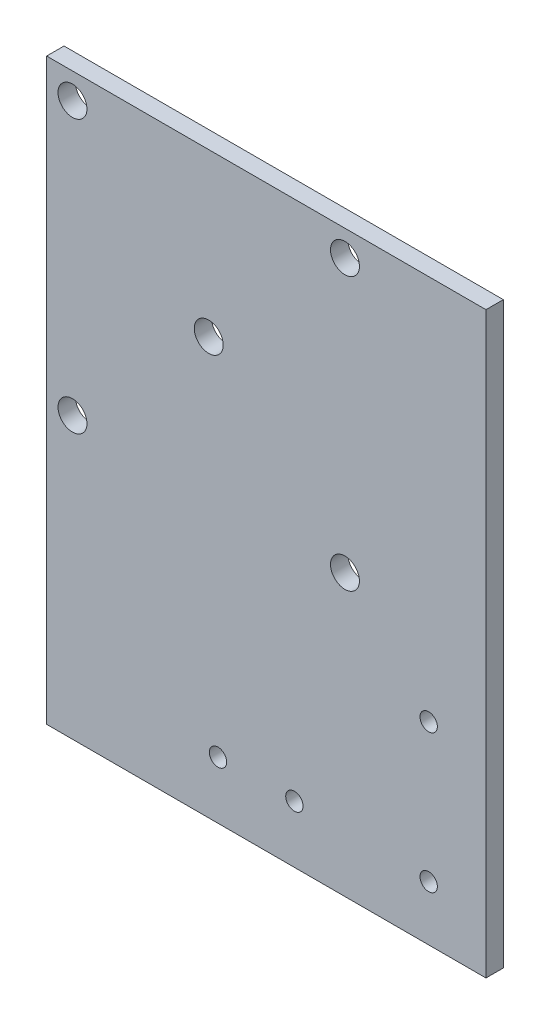
SolidWorks part; units mm, degrees
ref_plane "Front Plane" through (0, 0, 0) normal (0, 0, 1) x (1, 0, 0)
ref_plane "Top Plane" through (0, 0, 0) normal (0, 1, 0) x (1, 0, 0)
ref_plane "Right Plane" through (0, 0, 0) normal (1, 0, 0) x (0, 0, -1)
sketch "Sketch1" plane through (0, 0, 0) normal (0, 0, 1) x (1, 0, 0)
  line L1 (0, 0) -> (75.9, 0)
  line L2 (0, 0) -> (0, 100)
  line L3 (0, 100) -> (75.9, 100)
  line L4 (75.9, 0) -> (75.9, 100)
  dimension "D1" = 75.9
  dimension "D2" = 100
extrude "Boss-Extrude1" add sketch "Sketch1" along normal blind 3
sketch "Sketch2" plane through (0, 0, 0) normal (0, 0, -1) x (-1, 0, 0)
  circle A0 centre (-51.5386, 95.5386) radius 2.5
  circle A1 centre (-4.4614, 95.5386) radius 2.5
  circle A2 centre (-4.4614, 48.4614) radius 2.5
  circle A3 centre (-51.5386, 48.4614) radius 2.5
  dimension "D1" = 5
extrude "Cut-Extrude1" cut sketch "Sketch2" against normal blind 10
sketch "Sketch5" plane through (0, 0, 3) normal (0, 0, 1) x (1, 0, 0)
  line L0 (66, 0) -> (66, 100) construction
  line L1 (0, 0) -> (75.9, 0) construction
  line L2 (75.9, 100) -> (0, 100) construction
  line L3 (64.0784, 0) -> (67.9216, 0) construction
  line L4 (67.9216, 55.9706) -> (67.9216, -1564.0294) construction
  line L6 (64.0784, 55.9706) -> (64.0784, -1564.0294) construction
  circle A0 centre (66, 33.3914) radius 1.5
  circle A1 centre (66, 9.471) radius 1.5
  point P11 (66, 0)
  dimension "D1" = 3
extrude "Cut-Extrude2" cut sketch "Sketch5" against normal blind 10
sketch "Sketch7" plane through (0, 0, 0) normal (0, 0, -1) x (-1, 0, 0)
  circle A0 centre (-29.6, 9.9) radius 1.5
  circle A1 centre (-42.8, 9.9) radius 1.5
extrude "Cut-Extrude3" cut sketch "Sketch7" against normal blind 19.8
sketch "Sketch8" plane through (0, 0, 0) normal (0, 0, -1) x (-1, 0, 0)
  circle A0 centre (-28, 72) radius 2.5
  dimension "D1" = 5
extrude "Cut-Extrude4" cut sketch "Sketch8" against normal blind 10
